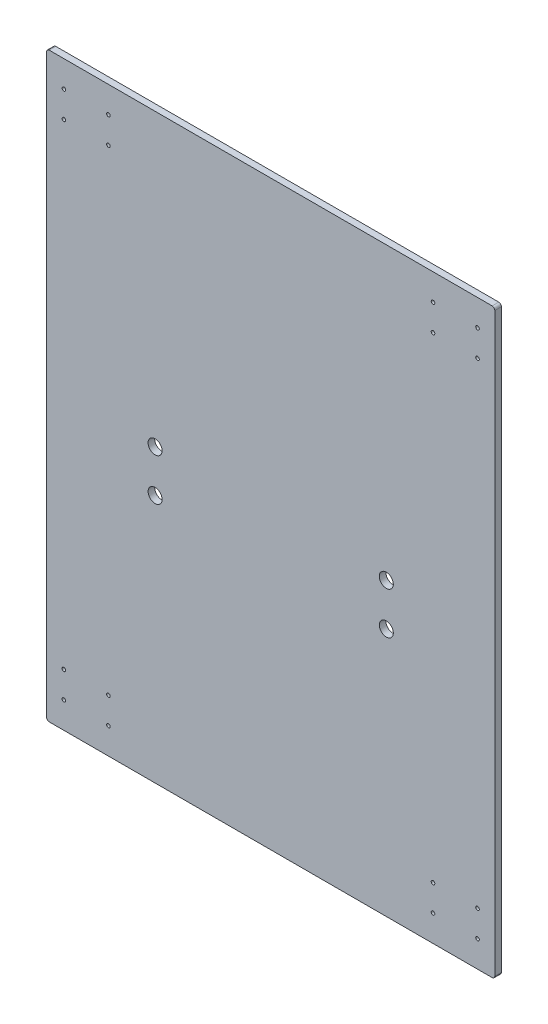
SolidWorks part; units mm, degrees
material "Plain Carbon Steel"
ref_plane "Front Plane" through (0, 0, 0) normal (0, 0, 1) x (1, 0, 0)
ref_plane "Top Plane" through (0, 0, 0) normal (0, 1, 0) x (1, 0, 0)
ref_plane "Right Plane" through (0, 0, 0) normal (1, 0, 0) x (0, 0, -1)
sketch "Sketch1" plane through (0, 0, 0) normal (0, 0, 1) x (1, 0, 0)
  line L0 (355.6, -484.2272) -> (0, 0) construction
  line L1 (0, 0) -> (0, 38.1) construction
  line L2 (393.7, -522.3669) -> (-38.1, -522.3669)
  line L3 (393.7, -522.3669) -> (393.7, 38.1)
  line L4 (393.7, 38.1) -> (-38.1, 38.1)
  line L5 (-38.1, -522.3669) -> (-38.1, 38.1)
  line L6 (393.7, -522.3669) -> (-38.1, 38.1) construction
  line L7 (393.7, 38.1) -> (-38.1, -522.3669) construction
  line L8 (-25.4, -21.4312) -> (-25.4, 21.4312) construction
  line L9 (0, 0) -> (-38.1, 0) construction
  point P4 (177.8, -242.1334)
  dimension "D1" = 12.7
extrude "Boss-Extrude1" add sketch "Sketch1" along normal blind 6.35
fillet "Fillet1" radius 2.54 4 edges at (393.7, 38.1, 3.175) (393.7, -522.3669, 3.175) (-38.1, -522.3669, 3.175) (-38.1, 38.1, 3.175)
sketch "Sketch3" plane through (0, 0, 0) normal (0, 0, -1) x (-1, 0, 0)
  line L0 (-177.8, 38.1) -> (-177.8, -522.3669) construction
  line L1 (-391.16, 38.1) -> (35.56, 38.1) construction
  line L2 (35.56, -522.3669) -> (-391.16, -522.3669) construction
  line L3 (-177.8, -262.14) -> (-289.1714, -262.14) construction
  line L4 (-289.1714, -241.82) -> (-289.1714, -282.46) construction
  point P8 (-289.1714, -241.82)
  point P9 (-289.1714, -282.46)
  point P13 (-66.4286, -282.46)
  point P14 (-66.4286, -241.82)
  dimension "D1" = 40.64
  dimension "D2" = 279.92
  dimension "D3" = 222.7428
hole_wizard "1/2 Clearance Hole1" positions "Sketch3" profile "Sketch4" hole size "1/2" standard "ANSI Inch" end condition up to next
sketch "Sketch4" plane through (66.4286, -241.82, 0) normal (1, 0, 0) x (0, 1, 0)
  line L0 (0, 0) -> (0, 6.35)
  line L1 (0, 6.35) -> (6.7462, 6.35)
  line L2 (6.7462, 6.35) -> (6.7462, 0)
  line L5 (6.7462, 0) -> (0, 0)
  line L11 (0, -6.35) -> (0, 107.95) construction
  dimension "Thru Hole Dia." = 13.4925
  dimension "Thru Hole Depth" = 6.35
sketch "Sketch6" plane through (0, 0, 0) normal (0, 0, -1) x (-1, 0, 0)
  line L0 (-393.7, -519.8269) -> (-393.7, 35.56) construction
  line L1 (-391.16, 38.1) -> (35.56, 38.1) construction
  line L2 (-177.8, 38.1) -> (-177.8, -522.3669) construction
  line L3 (35.56, -522.3669) -> (-391.16, -522.3669) construction
  line L4 (38.1, -242.1334) -> (-393.7, -242.1334) construction
  line L5 (38.1, 35.56) -> (38.1, -519.8269) construction
  point P0 (-377.0376, 12.7)
  point P1 (-377.0376, -12.7)
  point P2 (-334.1624, 12.7)
  point P3 (-334.1624, -12.7)
  point P16 (-21.4376, -12.7)
  point P17 (21.4376, -12.7)
  point P18 (21.4376, 12.7)
  point P19 (-21.4376, 12.7)
  point P20 (-21.4376, -496.9669)
  point P21 (21.4376, -496.9669)
  point P22 (21.4376, -471.5669)
  point P23 (-21.4376, -471.5669)
  point P24 (-334.1624, -471.5669)
  point P25 (-334.1624, -496.9669)
  point P26 (-377.0376, -471.5669)
  point P27 (-377.0376, -496.9669)
  dimension "D1" = 16.6624
  dimension "D2" = 25.4
  dimension "D3" = 25.4
  dimension "D4" = 42.8752
hole_wizard "#5 Clearance Hole1" positions "Sketch6" profile "Sketch7" hole size "#5" standard "ANSI Inch" end condition up to next
sketch "Sketch7" plane through (377.0376, 12.7, 0) normal (1, 0, 0) x (0, 1, 0)
  line L0 (0, 0) -> (0, 6.35)
  line L1 (0, 6.35) -> (1.7272, 6.35)
  line L2 (1.7272, 6.35) -> (1.7272, 0)
  line L5 (1.7272, 0) -> (0, 0)
  line L11 (0, -6.35) -> (0, 107.95) construction
  dimension "Thru Hole Dia." = 3.4544
  dimension "Thru Hole Depth" = 6.35
